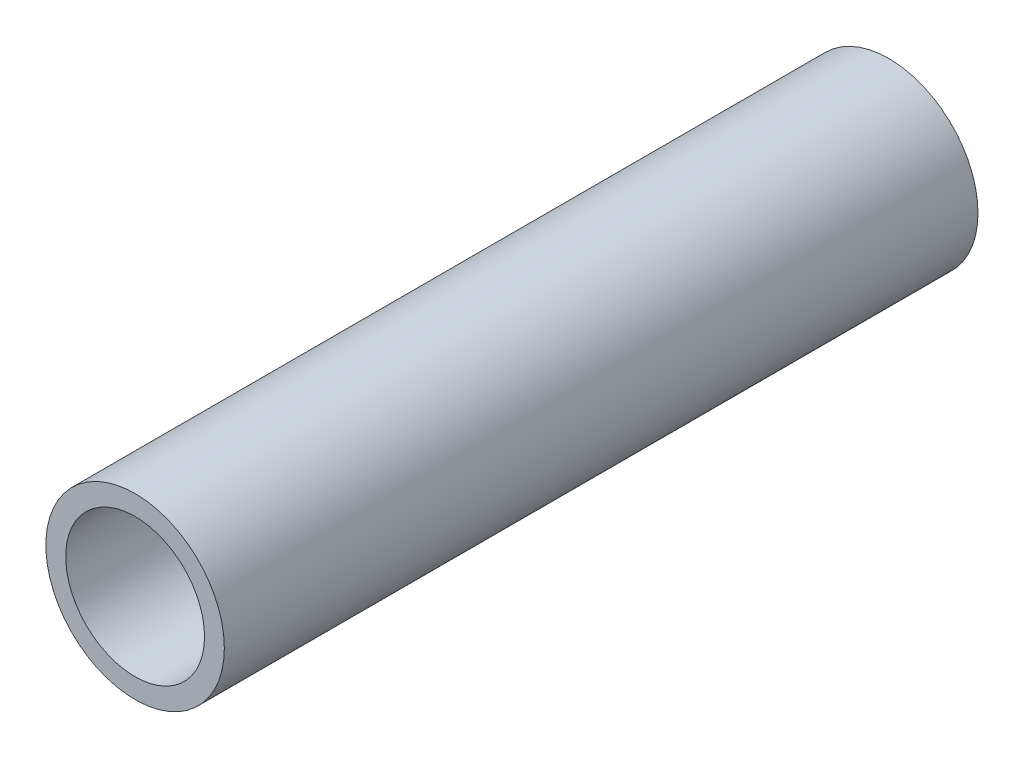
SolidWorks part; units mm, degrees
ref_plane "前视基准面" through (0, 0, 0) normal (0, 0, 1) x (1, 0, 0)
ref_plane "上视基准面" through (0, 0, 0) normal (0, 1, 0) x (1, 0, 0)
ref_plane "右视基准面" through (0, 0, 0) normal (1, 0, 0) x (0, 0, -1)
other "Configuration Table"
sketch "草图1" plane through (0, 0, 0) normal (0, 0, 1) x (1, 0, 0)
  circle A0 centre (0, 0) radius 9
  circle A1 centre (0, 0) radius 7
  dimension "D1" = 18
  dimension "D2" = 14
extrude "凸台-拉伸1" add sketch "草图1" along normal blind 76
